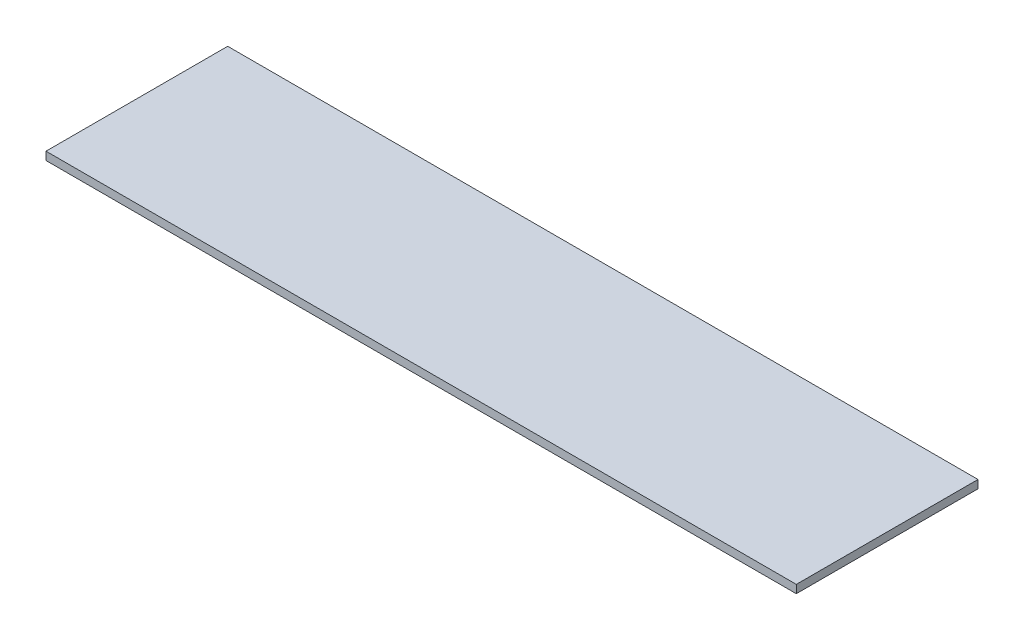
SolidWorks part; units mm, degrees
ref_plane "Front Plane" through (0, 0, 0) normal (0, 0, 1) x (1, 0, 0)
ref_plane "Top Plane" through (0, 0, 0) normal (0, 1, 0) x (1, 0, 0)
ref_plane "Right Plane" through (0, 0, 0) normal (1, 0, 0) x (0, 0, -1)
sketch "Sketch1" plane through (0, 0, 0) normal (0, 1, 0) x (1, 0, 0)
  line L1 (-92.5, 22.4) -> (92.5, 22.4)
  line L2 (-92.5, 22.4) -> (-92.5, -22.4)
  line L3 (-92.5, -22.4) -> (92.5, -22.4)
  line L4 (92.5, 22.4) -> (92.5, -22.4)
  line L5 (-92.5, 22.4) -> (92.5, -22.4) construction
  line L6 (-92.5, -22.4) -> (92.5, 22.4) construction
  point P0 (0, 0)
  dimension "D1" = 185
  dimension "D2" = 44.8
extrude "Boss-Extrude1" add sketch "Sketch1" along normal blind 2
